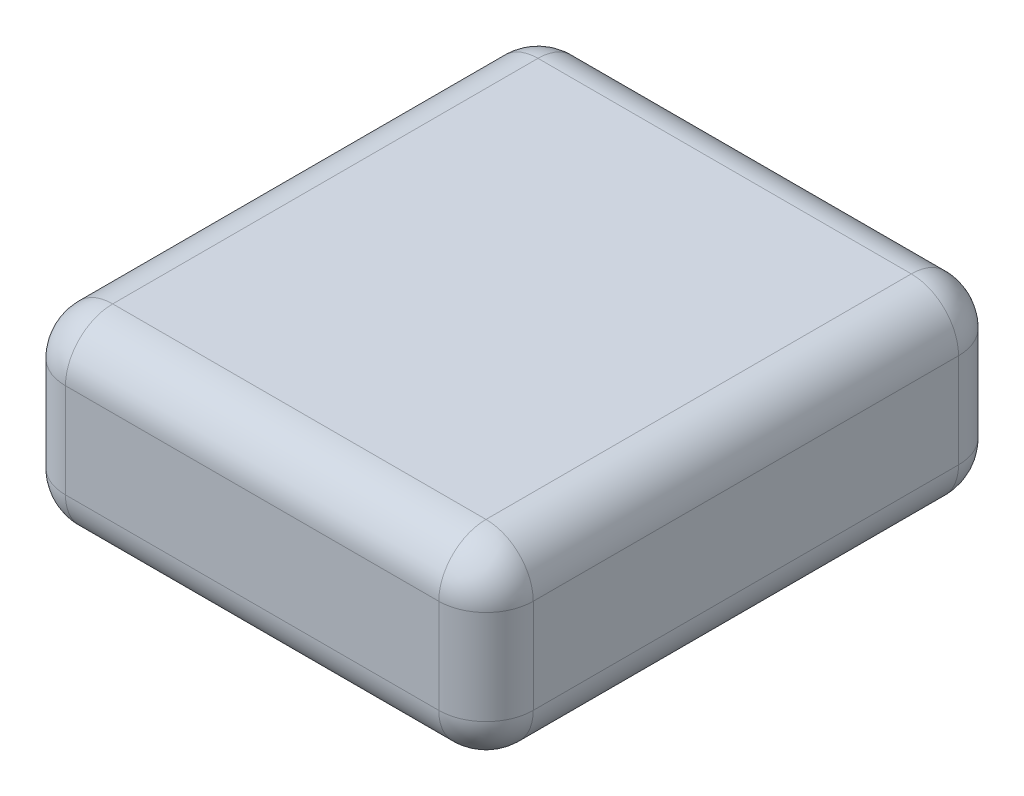
SolidWorks part; units mm, degrees
ref_plane "Alzado" through (0, 0, 0) normal (0, 0, 1) x (1, 0, 0)
ref_plane "Planta" through (0, 0, 0) normal (0, 1, 0) x (1, 0, 0)
ref_plane "Vista lateral" through (0, 0, 0) normal (1, 0, 0) x (0, 0, -1)
sketch "Croquis1" plane through (0, 0, 0) normal (0, 0, 1) x (1, 0, 0)
  line L1 (-25.1009, 8) -> (-5.3009, 8)
  line L2 (-25.1009, 8) -> (-25.1009, 0)
  line L3 (-25.1009, 0) -> (-5.3009, 0)
  line L4 (-5.3009, 8) -> (-5.3009, 0)
  dimension "D1" = 8
  dimension "D2" = 19.8
extrude "Saliente-Extruir1" add sketch "Croquis1" along normal blind 22
fillet "Redondeo1" radius 2 12 edges at (-15.2009, 0, 0) (-25.1009, 0, 11) (-25.1009, 4, 0) (-5.3009, 0, 11) (-5.3009, 4, 0) (-5.3009, 4, 22) (-15.2009, 0, 22) (-25.1009, 4, 22) (-5.3009, 8, 11) (-15.2009, 8, 22) (-25.1009, 8, 11) (-15.2009, 8, 0)
